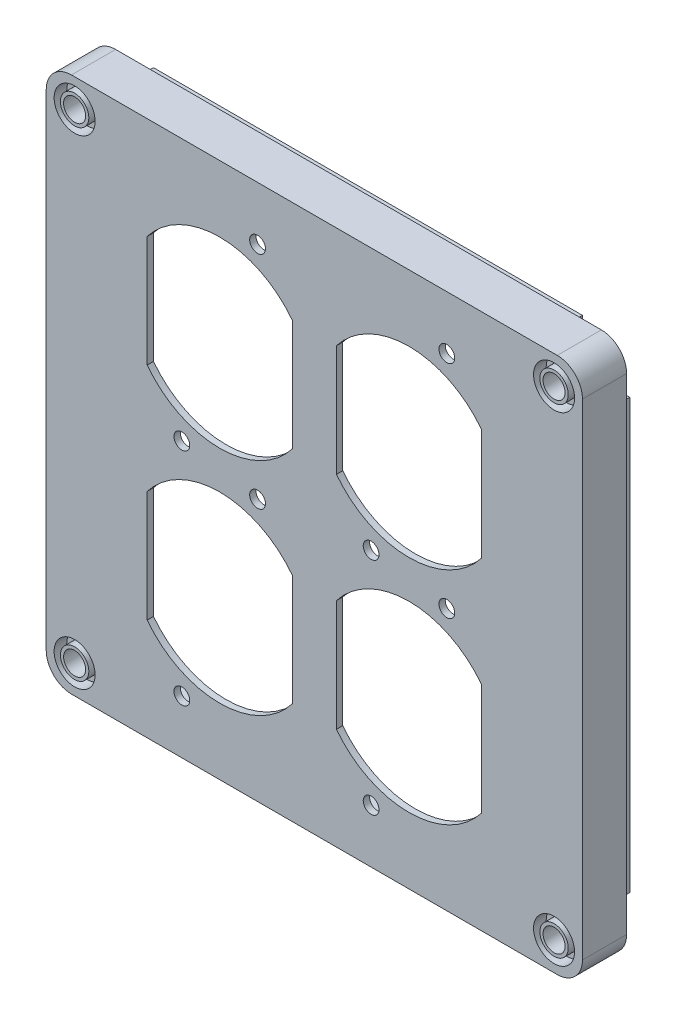
SolidWorks part; units mm, degrees
ref_plane "Front Plane" through (0, 0, 0) normal (0, 0, 1) x (1, 0, 0)
ref_plane "Top Plane" through (0, 0, 0) normal (0, 1, 0) x (1, 0, 0)
ref_plane "Right Plane" through (0, 0, 0) normal (1, 0, 0) x (0, 0, -1)
sketch "Sketch1" plane through (0, 0, 0) normal (0, 0, 1) x (1, 0, 0)
  line L1 (-42.5, -42.5) -> (42.5, -42.5)
  line L2 (-42.5, -42.5) -> (-42.5, 42.5)
  line L3 (-42.5, 42.5) -> (42.5, 42.5)
  line L4 (42.5, -42.5) -> (42.5, 42.5)
  line L5 (-42.5, -42.5) -> (42.5, 42.5) construction
  line L6 (-42.5, 42.5) -> (42.5, -42.5) construction
  point P0 (0, 0)
  dimension "D1" = 85
  dimension "D2" = 85
extrude "Boss-Extrude1" add sketch "Sketch1" along normal blind 7
sketch "Sketch8" plane through (0, 0, 0) normal (0, 0, -1) x (-1, 0, 0)
  line L14 (40.5, -40.5) -> (40.5, 40.5)
  line L15 (-40.5, -40.5) -> (40.5, -40.5)
  line L16 (-40.5, 40.5) -> (-40.5, -40.5)
  line L17 (40.5, 40.5) -> (-40.5, 40.5)
  line L18 (40.5, -37.5) -> (40.5, 37.5)
  line L19 (-37.5, -40.5) -> (37.5, -40.5)
  line L20 (-40.5, 37.5) -> (-40.5, -37.5)
  line L21 (37.5, 40.5) -> (-37.5, 40.5)
  arc A0 (-37.5, -40.5) -> (-40.5, -37.5) centre (-37.5, -37.5) cw
  arc A1 (40.5, -37.5) -> (37.5, -40.5) centre (37.5, -37.5) cw
  arc A2 (40.5, 37.5) -> (37.5, 40.5) centre (37.5, 37.5) ccw
  arc A3 (-40.5, 37.5) -> (-37.5, 40.5) centre (-37.5, 37.5) cw
  dimension "D2" = 3
  dimension "D1" = 2
extrude "Cut-Extrude4" cut sketch "Sketch8" against normal offset from surface (6 mm away) 1 up to face at (0, 0, 7)
fillet "Fillet4" radius 4 4 edges at (42.5, 42.5, 3.5) (42.5, -42.5, 3.5) (-42.5, 42.5, 3.5) (-42.5, -42.5, 3.5)
sketch "Sketch2" plane through (0, 0, 7) normal (0, 0, 1) x (1, 0, 0)
  line L2 (-26.5, 8.6682) -> (-26.5, 26.3318)
  line L4 (-3.5, 8.6682) -> (-3.5, 26.3318)
  line L5 (-26.5, 8.6682) -> (-3.5, 26.3318) construction
  line L6 (-26.5, 26.3318) -> (-3.5, 8.6682) construction
  arc A0 (-26.5, 26.3318) -> (-3.5, 26.3318) centre (-15, 17.5) cw
  arc A1 (-26.5, 8.6682) -> (-3.5, 8.6682) centre (-15, 17.5) ccw
  point P0 (-15, 17.5)
  point P7 (-15, 3)
  point P9 (-15, 32)
  dimension "D1" = 23
  dimension "D2" = 17.5
  dimension "D3" = 15
  dimension "D4" = 29
extrude "Cut-Extrude1" cut sketch "Sketch2" against normal through all
sketch "Sketch35" plane through (0, 0, 6) normal (0, 0, -1) x (-1, 0, 0)
  line L0 (-37.5, 40.5) -> (37.5, 40.5) construction
  line L1 (3.5, 40.5) -> (26.5, 40.5)
  line L2 (3.5, 40.5) -> (3.5, -40.5)
  line L3 (3.5, -40.5) -> (26.5, -40.5)
  line L4 (26.5, 40.5) -> (26.5, -40.5)
  line L5 (37.5, -40.5) -> (-37.5, -40.5) construction
  line L6 (3.5, 26.3318) -> (3.5, 8.6682) construction
  line L7 (26.5, 8.6682) -> (26.5, 26.3318) construction
sketch "Sketch3" plane through (0, 0, 7) normal (0, 0, 1) x (1, 0, 0)
  line L0 (-15, 32) -> (-15, 3) construction
  circle A0 centre (-9, 34) radius 1.25
  circle A1 centre (-21, 1) radius 1.25
  arc A2 (-3.5, 26.3318) -> (-26.5, 26.3318) centre (-15, 17.5) ccw construction
  arc A3 (-26.5, 8.6682) -> (-3.5, 8.6682) centre (-15, 17.5) ccw construction
  point P12 (-15, 17.5)
  dimension "D3" = 2.5
  dimension "D1" = 6
  dimension "D2" = 6
  dimension "D4" = 16.5
  dimension "D5" = 16.5
extrude "Cut-Extrude6" cut sketch "Sketch3" against normal through all
pattern_linear "LPattern1" count 2 spacing 35 along (0, -1, 0) count 2 spacing 30 along (1, 0, 0) of "Cut-Extrude1", "Cut-Extrude6"
sketch "Sketch14" plane through (0, 0, 7) normal (0, 0, 1) x (1, 0, 0)
  line L0 (-42.5, 38.5) -> (-42.5, -38.5) construction
  line L1 (-38, 33.5) -> (-42.5, 33.5)
  line L2 (-42.5, 38.5) -> (-42.5, -38.5) construction
  line L3 (-42.5, 33.5) -> (-42.5, 38)
  line L4 (-38, 42.5) -> (-33.5, 42.5)
  line L5 (-33.5, 42.5) -> (-33.5, 38)
  arc A0 (-38, 42.5) -> (-42.5, 38) centre (-38, 38) ccw
  arc A2 (-38, 33.5) -> (-33.5, 38) centre (-38, 38) ccw
  dimension "D1" = 38
  dimension "D2" = 38
extrude "Boss-Extrude6" add sketch "Sketch14" against normal up to surface (7 mm away) up to face at (0, 0, 0)
sketch "Sketch15" plane through (0, 0, 0) normal (0, 0, -1) x (-1, 0, 0)
  circle A0 centre (38, 38) radius 1.75
  arc A1 (33.5, 38) -> (38, 33.5) centre (38, 38) ccw construction
  dimension "D1" = 3.5
extrude "Cut-Extrude7" cut sketch "Sketch15" against normal through all
sketch "Sketch30" plane through (0, 0, 7) normal (0, 0, 1) x (1, 0, 0)
  circle A0 centre (-38, 38) radius 3.25
  dimension "D1" = 6.5
extrude "Cut-Extrude8" cut sketch "Sketch30" against normal offset from surface (2 mm away) 5 up to face at (-39.75, 38, 0)
sketch "Sketch31" plane through (0, 0, 5) normal (0, 0, 1) x (1, 0, 0)
  circle A0 centre (-38, 38) radius 1.75 construction
  circle A1 centre (-38, 38) radius 1.75
extrude "Extrude-Thin2" add sketch "Sketch31" along normal up to surface (2 mm away) thin
mirror "Mirror3" about plane through (0, 0, 0) normal (1, 0, 0) of "Extrude-Thin2", "Cut-Extrude8", "Boss-Extrude6", "Cut-Extrude7"
mirror "Mirror4" about plane through (0, 0, 0) normal (0, 1, 0) of "Mirror3", "Boss-Extrude6", "Cut-Extrude7", "Cut-Extrude8", "Extrude-Thin2"
other "Move Face1" face at (-35.284, -35.284, 3) face at (-33.5, -39.25, 3) face at (-39.25, -33.5, 3) face at (33.5, -39.25, 3) face at (39.25, -33.5, 3) face at (35.284, -35.284, 3) face at (33.5, 39.25, 3) face at (35.284, 35.284, 3) face at (39.25, 33.5, 3) face at (-39.25, 33.5, 3) face at (-35.284, 35.284, 3) face at (-33.5, 39.25, 3) parameters "D1"=0.5
sketch "Sketch29" plane through (0, 0, 0) normal (0, 0, -1) x (-1, 0, 0)
  line L0 (33, 40.5) -> (-33, 40.5) construction
  line L1 (-33, 38) -> (-33, 40.5) construction
  line L2 (-40.5, 33) -> (-38, 33) construction
  line L3 (-40.5, 33) -> (-40.5, -33) construction
  line L4 (-40.5, -33) -> (-38, -33) construction
  line L5 (-33, -38) -> (-33, -40.5) construction
  line L6 (-33, -40.5) -> (33, -40.5) construction
  line L7 (33, -38) -> (33, -40.5) construction
  line L8 (40.5, -33) -> (38, -33) construction
  line L9 (40.5, -33) -> (40.5, 33) construction
  line L10 (40.5, 33) -> (38, 33) construction
  line L11 (33, 38) -> (33, 40.5) construction
  line L12 (33, 40.5) -> (-33, 40.5)
  line L13 (-33, 38) -> (-33, 40.5)
  line L14 (-40.5, 33) -> (-38, 33)
  line L15 (-40.5, 33) -> (-40.5, -33)
  line L16 (-40.5, -33) -> (-38, -33)
  line L17 (-33, -38) -> (-33, -40.5)
  line L18 (-33, -40.5) -> (33, -40.5)
  line L19 (33, -38) -> (33, -40.5)
  line L20 (40.5, -33) -> (38, -33)
  line L21 (40.5, -33) -> (40.5, 33)
  line L22 (40.5, 33) -> (38, 33)
  line L23 (33, 38) -> (33, 40.5)
  arc A0 (-38, 33) -> (-33, 38) centre (-38, 38) ccw construction
  arc A1 (-33, -38) -> (-38, -33) centre (-38, -38) ccw construction
  arc A2 (38, -33) -> (33, -38) centre (38, -38) ccw construction
  arc A3 (33, 38) -> (38, 33) centre (38, 38) ccw construction
  arc A4 (-38, 33) -> (-33, 38) centre (-38, 38) ccw
  arc A5 (-33, -38) -> (-38, -33) centre (-38, -38) ccw
  arc A6 (38, -33) -> (33, -38) centre (38, -38) ccw
  arc A7 (33, 38) -> (38, 33) centre (38, 38) ccw
extrude "Extrude-Thin1" add sketch "Sketch29" along normal blind 1.5 thin
